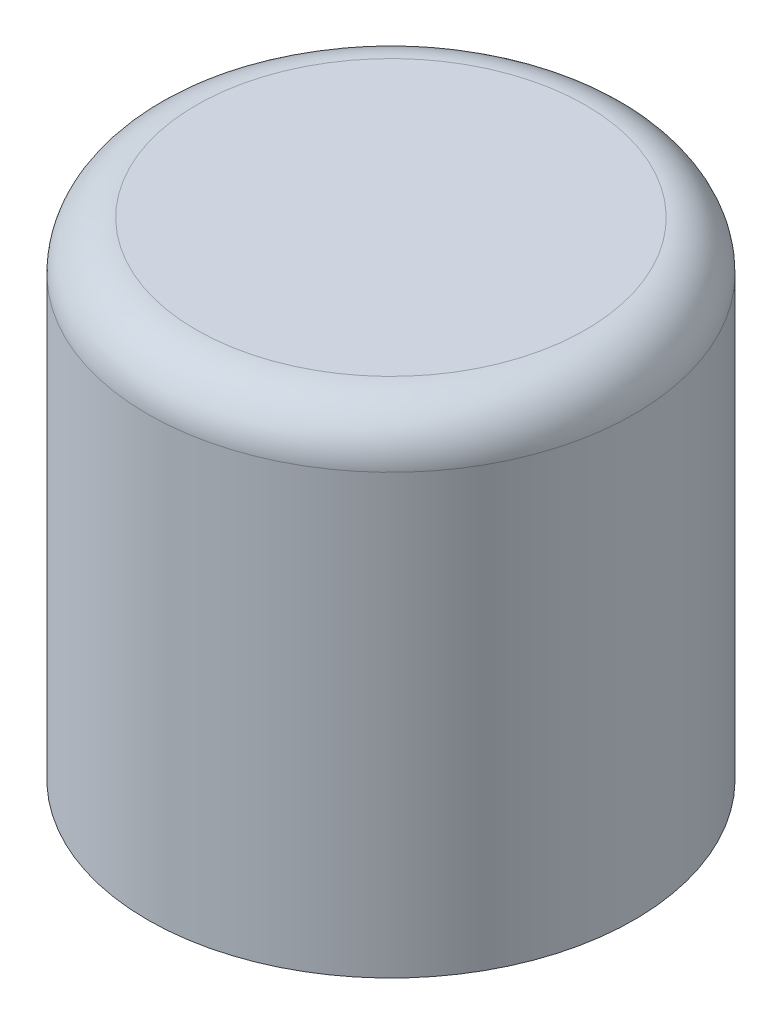
SolidWorks part; units mm, degrees
ref_plane "Front Plane" through (0, 0, 0) normal (0, 0, 1) x (1, 0, 0)
ref_plane "Top Plane" through (0, 0, 0) normal (0, 1, 0) x (1, 0, 0)
ref_plane "Right Plane" through (0, 0, 0) normal (1, 0, 0) x (0, 0, -1)
sketch "Sketch1" plane through (0, 0, 0) normal (0, 1, 0) x (1, 0, 0)
  circle A0 centre (0, 0) radius 15
  dimension "D1" = 30
extrude "Boss-Extrude1" add sketch "Sketch1" along normal blind 30
fillet "Fillet1" radius 3 1 edges at (0, 30, 15)
